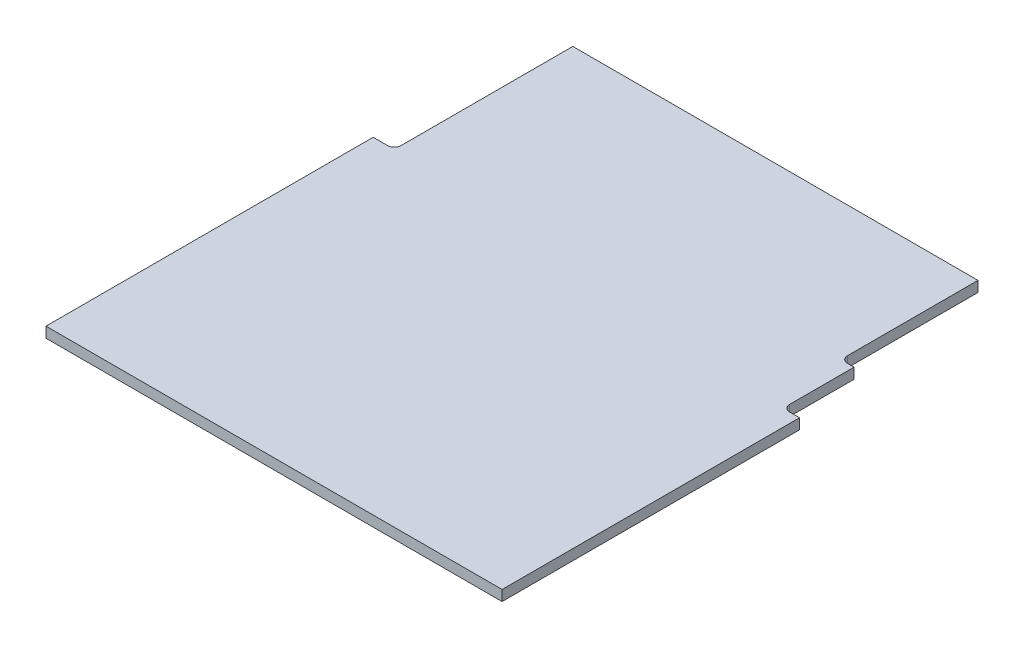
SolidWorks part; units mm, degrees
ref_plane "Front" through (0, 0, 0) normal (0, 0, 1) x (1, 0, 0)
ref_plane "Top" through (0, 0, 0) normal (0, 1, 0) x (1, 0, 0)
ref_plane "Right" through (0, 0, 0) normal (1, 0, 0) x (0, 0, -1)
sketch "Sketch1" plane through (0, 0, 0) normal (0, 1, 0) x (1, 0, 0)
  line L0 (-34.5, -9) -> (-34.5, -16) construction
  line L1 (-34.5, -9) -> (34.5, -9)
  line L2 (-34.5, -9) -> (-34.5, 67.5) construction
  line L3 (-34.5, 67.5) -> (34.5, 67.5) construction
  line L4 (34.5, -9) -> (34.5, 67.5) construction
  line L5 (-34.5, -16) -> (34.5, -16) construction
  line L6 (34.5, -16) -> (34.5, -9) construction
  line L7 (34.5, -9) -> (34.5, 36)
  line L8 (34.5, 36) -> (32, 36) construction
  line L9 (32, 36) -> (32, 46.75) construction
  line L10 (32, 46.75) -> (30, 46.75) construction
  line L11 (30, 46.75) -> (30, 67.5) construction
  line L12 (30, 67.5) -> (-31.3, 67.5)
  line L13 (-31.3, 67.5) -> (-31.3, 40.5) construction
  line L14 (-31.3, 40.5) -> (-34.5, 40.5) construction
  line L15 (-34.5, 40.5) -> (-34.5, -9)
  line L16 (30, 67.5) -> (30, 47.75)
  line L17 (31, 46.75) -> (32, 46.75)
  line L18 (32, 46.75) -> (32, 37)
  line L19 (32.94, 36) -> (34.5, 36)
  line L20 (-31.3, 67.5) -> (-31.3, 41.5)
  line L21 (-32.2185, 40.5) -> (-34.5, 40.5)
  arc A0 (30, 47.75) -> (31, 46.75) centre (31, 47.75) ccw
  arc A1 (32, 37) -> (32.94, 36) centre (33.0019, 37) ccw
  arc A2 (-31.3, 41.5) -> (-32.2185, 40.5) centre (-32.3036, 41.5) cw
extrude "FR4" add sketch "Sketch1" along normal blind 1.5875
